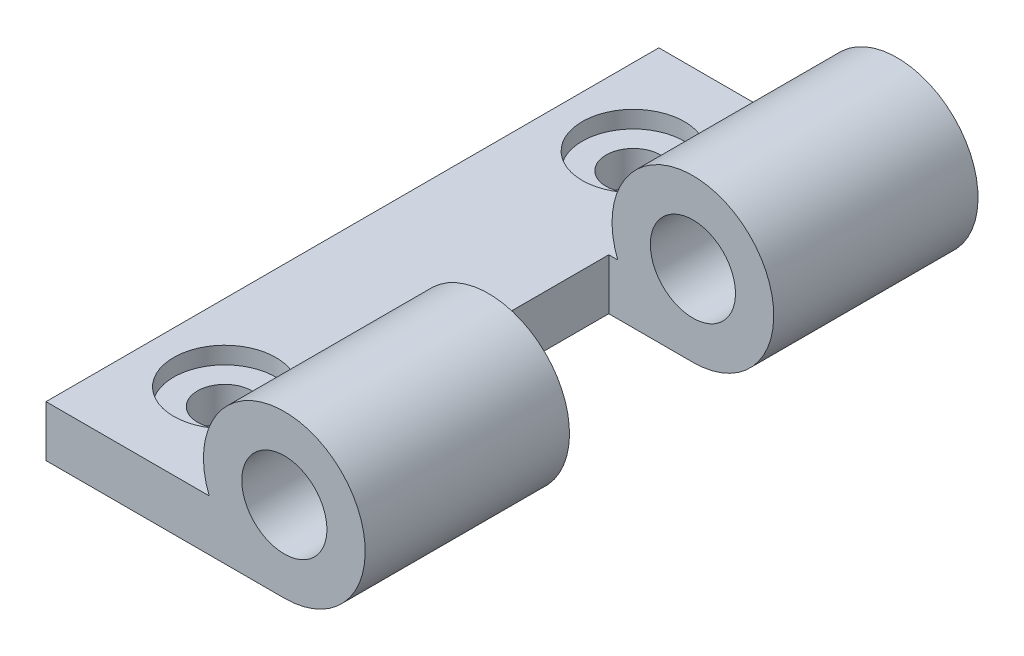
SolidWorks part; units mm, degrees
ref_plane "前视基准面" through (0, 0, 0) normal (0, 0, 1) x (1, 0, 0)
ref_plane "上视基准面" through (0, 0, 0) normal (0, 1, 0) x (1, 0, 0)
ref_plane "右视基准面" through (0, 0, 0) normal (1, 0, 0) x (0, 0, -1)
sketch "草图1" plane through (0, 0, 0) normal (0, 1, 0) x (1, 0, 0)
  line L1 (0, 0) -> (14, 0)
  line L2 (0, 0) -> (0, -36)
  line L3 (0, -36) -> (14, -36)
  line L4 (14, 0) -> (14, -36)
  dimension "D1" = 36
  dimension "D2" = 14
extrude "凸台-拉伸1" add sketch "草图1" along normal blind 3
sketch "草图2" plane through (0, 0, 0) normal (0, 0, -1) x (-1, 0, 0)
  line L2 (-14, 3) -> (-14, 0) construction
  line L3 (-14, 0) -> (0, 0) construction
  circle A0 centre (-14, 4.75) radius 4.75
  dimension "D1" = 0
  dimension "D2" = 9.5
extrude "凸台-拉伸2" add sketch "草图2" against normal blind 12
sketch "草图3" plane through (0, 0, 36) normal (0, 0, 1) x (1, 0, 0)
  line L2 (0, 0) -> (14, 0) construction
  line L3 (14, 3) -> (14, 0) construction
  circle A0 centre (14, 4.75) radius 4.75
  dimension "D1" = 9.5
  dimension "D2" = 0
extrude "凸台-拉伸3" add sketch "草图3" against normal blind 12
sketch "草图4" plane through (0, 0, 0) normal (0, 0, -1) x (-1, 0, 0)
  circle A0 centre (-14, 4.75) radius 2.5
  arc A1 (-9.5841, 3) -> (-14, 0) centre (-14, 4.75) ccw construction
  dimension "D1" = 0
  dimension "D2" = 5
extrude "切除-拉伸1" cut sketch "草图4" against normal blind 51
ref_plane "基准面4" through (0, 0, 24) normal (0, 0, -1) x (-1, 0, 0)
sketch "草图5" plane through (0, 0, 24) normal (0, 0, -1) x (-1, 0, 0)
  line L1 (-9.0578, 8.0041) -> (-17.9515, 8.0041)
  line L2 (-9.0578, 8.0041) -> (-9.0578, -2.693)
  line L3 (-9.0578, -2.693) -> (-17.9515, -2.693)
  line L4 (-17.9515, 8.0041) -> (-17.9515, -2.693)
extrude "切除-拉伸2" cut sketch "草图5" along normal up to surface (12 mm away) up to face at (14.1342, 4.9647, 12)
sketch "草图6" plane through (0, 3, 0) normal (0, 1, 0) x (1, 0, 0)
  line L0 (0, -36) -> (9.5841, -36) construction
  line L1 (0, 0) -> (0, -36) construction
  circle A0 centre (4.5, -6) radius 1.6
  circle A1 centre (4.5, -30) radius 1.6
  dimension "D1" = 3.2
  dimension "D2" = 24
  dimension "D3" = 6
  dimension "D4" = 4.5
extrude "切除-拉伸3" cut sketch "草图6" against normal blind 10
sketch "草图7" plane through (0, 3, 0) normal (0, 1, 0) x (1, 0, 0)
  circle A0 centre (4.5, -6) radius 3
  circle A1 centre (4.5, -30) radius 3
  dimension "D1" = 6
extrude "切除-拉伸4" cut sketch "草图7" against normal blind 1
